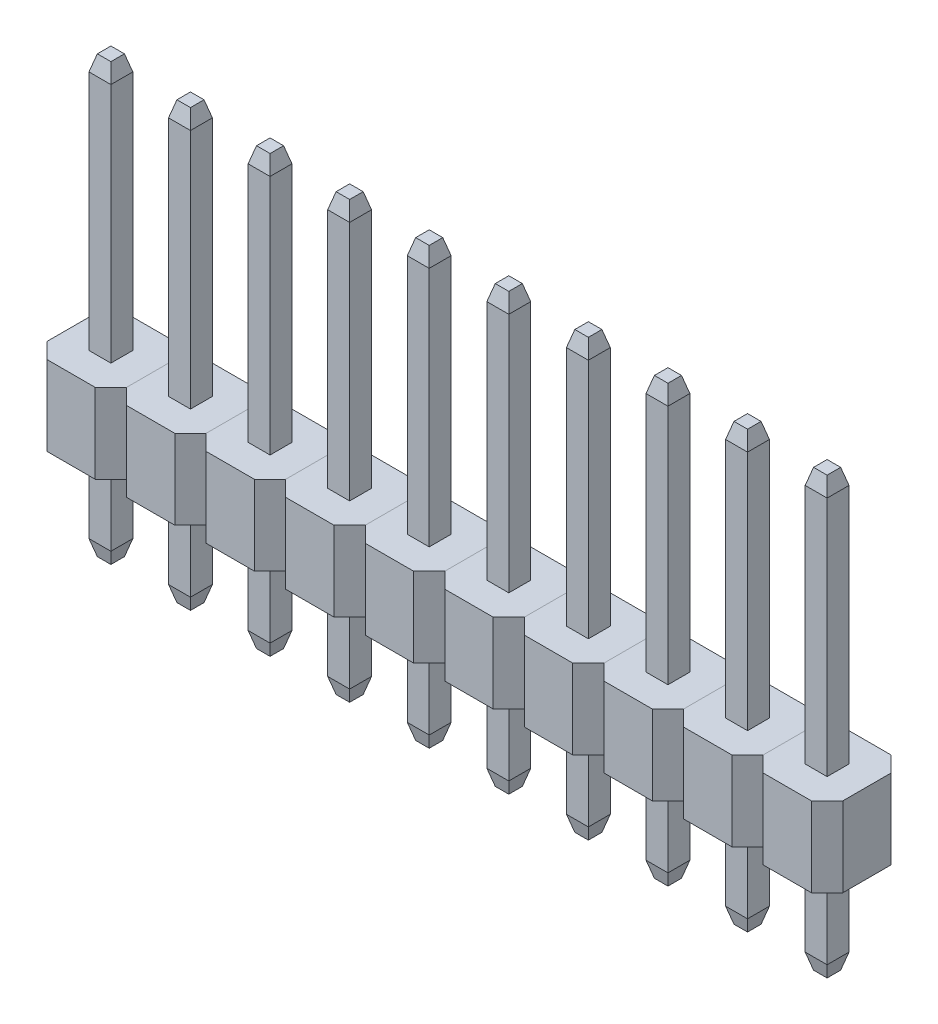
SolidWorks part; units mm, degrees
ref_plane "Front Plane" through (0, 0, 0) normal (0, 0, 1) x (1, 0, 0)
ref_plane "Top Plane" through (0, 0, 0) normal (0, 1, 0) x (1, 0, 0)
ref_plane "Right Plane" through (0, 0, 0) normal (1, 0, 0) x (0, 0, -1)
sketch "Sketch3" plane through (0, 0, 0) normal (0, 1, 0) x (1, 0, 0)
  line L1 (-1.27, 1.27) -> (1.27, 1.27)
  line L2 (-1.27, 1.27) -> (-1.27, -1.27)
  line L3 (-1.27, -1.27) -> (1.27, -1.27)
  line L4 (1.27, 1.27) -> (1.27, -1.27)
  line L5 (-1.27, 1.27) -> (1.27, -1.27) construction
  line L6 (-1.27, -1.27) -> (1.27, 1.27) construction
  line L7 (0.3175, -0.3175) -> (-0.3175, -0.3175)
  line L8 (0.3175, -0.3175) -> (0.3175, 0.3175)
  line L9 (0.3175, 0.3175) -> (-0.3175, 0.3175)
  line L10 (-0.3175, -0.3175) -> (-0.3175, 0.3175)
  line L11 (0.3175, -0.3175) -> (-0.3175, 0.3175) construction
  line L12 (0.3175, 0.3175) -> (-0.3175, -0.3175) construction
  point P0 (0, 0)
  point P7 (0, 0)
  dimension "D1" = 2.54
  dimension "D2" = 0.635
extrude "Boss-Extrude1" add sketch "Sketch3" along normal mid plane 2.54
chamfer "Chamfer1" distance 0.5 angle 45 4 edges at (-1.27, 0, 1.27) (-1.27, 0, -1.27) (1.27, 0, -1.27) (1.27, 0, 1.27)
sketch "Sketch5" plane through (0, 1.27, 0) normal (0, 1, 0) x (1, 0, 0)
  line L1 (0.35, -0.35) -> (-0.35, -0.35)
  line L2 (0.35, -0.35) -> (0.35, 0.35)
  line L3 (0.35, 0.35) -> (-0.35, 0.35)
  line L4 (-0.35, -0.35) -> (-0.35, 0.35)
  line L5 (0.35, -0.35) -> (-0.35, 0.35) construction
  line L6 (0.35, 0.35) -> (-0.35, -0.35) construction
  point P0 (0, 0)
  dimension "D1" = 0.7
extrude "Boss-Extrude2" add sketch "Sketch5" along normal blind 7.7 and the other way blind 5.2 separate body
sketch "Sketch6" plane through (0, 8.97, 0) normal (0, 1, 0) x (1, 0, 0)
  line L4 (-0.35, 0.35) -> (-0.35, -0.35)
  line L5 (-0.35, -0.35) -> (0.35, -0.35)
  line L6 (0.35, -0.35) -> (0.35, 0.35)
  line L7 (0.35, 0.35) -> (-0.35, 0.35)
  line L8 (-0.35, 0.35) -> (-0.35, -0.35)
  line L9 (-0.35, -0.35) -> (0.35, -0.35)
  line L10 (0.35, -0.35) -> (0.35, 0.35)
  line L11 (0.35, 0.35) -> (-0.35, 0.35)
  dimension "D1" = 0
extrude "Boss-Extrude3" add sketch "Sketch6" along normal blind 0.5 draft 15
sketch "Sketch7" plane through (0, -3.93, 0) normal (0, -1, 0) x (1, 0, 0)
  line L4 (-0.35, 0.35) -> (-0.35, -0.35)
  line L5 (-0.35, -0.35) -> (0.35, -0.35)
  line L6 (0.35, -0.35) -> (0.35, 0.35)
  line L7 (0.35, 0.35) -> (-0.35, 0.35)
  line L8 (-0.35, 0.35) -> (-0.35, -0.35)
  line L9 (-0.35, -0.35) -> (0.35, -0.35)
  line L10 (0.35, -0.35) -> (0.35, 0.35)
  line L11 (0.35, 0.35) -> (-0.35, 0.35)
  dimension "D1" = 0
extrude "Boss-Extrude4" add sketch "Sketch7" along normal blind 0.5 draft 15
pattern_linear "LPattern1" count 10 spacing 2.54 along (1, 0, 0) of "Boss-Extrude1", "Boss-Extrude2"
